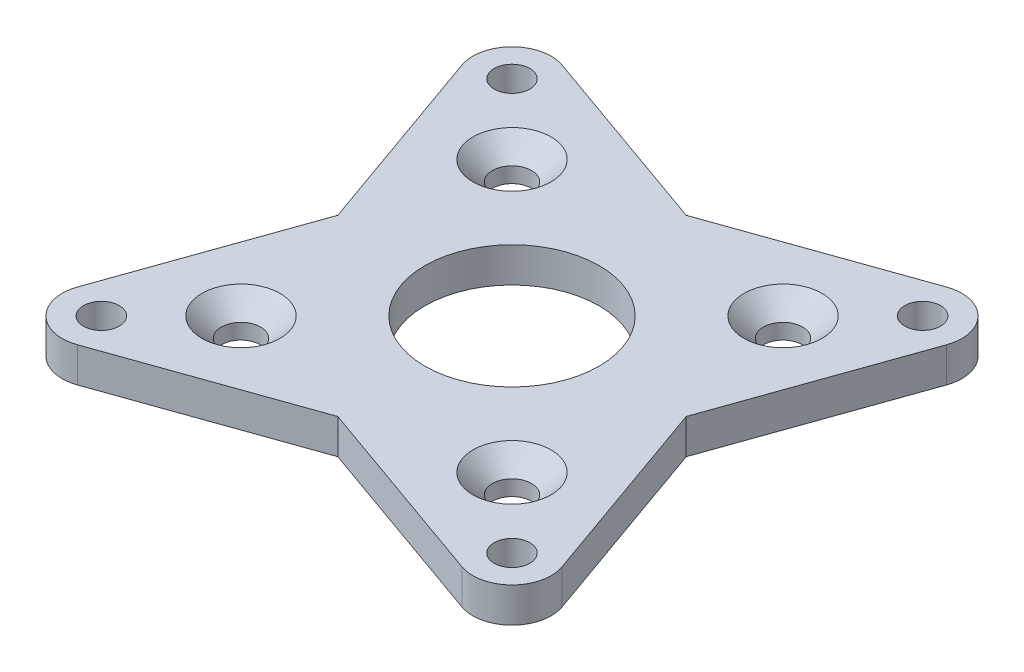
SolidWorks part; units mm, degrees
ref_plane "Alzado" through (0, 0, 0) normal (0, 0, 1) x (1, 0, 0)
ref_plane "Planta" through (0, 0, 0) normal (0, 1, 0) x (1, 0, 0)
ref_plane "Vista lateral" through (0, 0, 0) normal (1, 0, 0) x (0, 0, -1)
sketch "Sketch1" plane through (0, 0, 0) normal (0, 1, 0) x (1, 0, 0)
  line L1 (-35.65, -30) -> (35.65, -30)
  line L2 (-35.65, -30) -> (-35.65, 30)
  line L3 (-35.65, 30) -> (35.65, 30)
  line L4 (35.65, -30) -> (35.65, 30)
  line L5 (-35.65, -30) -> (35.65, 30) construction
  line L6 (-35.65, 30) -> (35.65, -30) construction
  point P0 (0, 0)
  dimension "D1" = 60
  dimension "D2" = 71.3
extrude "Boss-Extrude1" add sketch "Sketch1" along normal blind 4
sketch "Sketch2" plane through (0, 4, 0) normal (0, 1, 0) x (1, 0, 0)
  line L5 (-15.5563, -15.5563) -> (15.5563, -15.5563) construction
  line L6 (-15.5563, -15.5563) -> (-15.5563, 15.5563) construction
  line L7 (-15.5563, 15.5563) -> (15.5563, 15.5563) construction
  line L8 (15.5563, -15.5563) -> (15.5563, 15.5563) construction
  line L9 (-15.5563, -15.5563) -> (15.5563, 15.5563) construction
  line L10 (-15.5563, 15.5563) -> (15.5563, -15.5563) construction
  line L11 (-23.57, -23.57) -> (23.57, -23.57) construction
  line L12 (-23.57, -23.57) -> (-23.57, 23.57) construction
  line L13 (-23.57, 23.57) -> (23.57, 23.57) construction
  line L14 (23.57, -23.57) -> (23.57, 23.57) construction
  line L15 (-23.57, -23.57) -> (23.57, 23.57) construction
  line L16 (-23.57, 23.57) -> (23.57, -23.57) construction
  circle A2 centre (-15.5563, 15.5563) radius 2.05
  circle A3 centre (-23.57, 23.57) radius 2.05
  circle A4 centre (15.5563, 15.5563) radius 2.05
  circle A5 centre (23.57, 23.57) radius 2.05
  circle A6 centre (15.5563, -15.5563) radius 2.05
  circle A7 centre (23.57, -23.57) radius 2.05
  circle A8 centre (-15.5563, -15.5563) radius 2.05
  circle A9 centre (-23.57, -23.57) radius 2.05
  point P0 (0, 0)
  point P29 (0, 0)
  dimension "D1" = 47.14
  dimension "D2" = 44
  dimension "D3" = 4.1
  dimension "D4" = 4
extrude "Cut-Extrude1" cut sketch "Sketch2" against normal through all
sketch "Sketch3" plane through (0, 4, 0) normal (0, 1, 0) x (1, 0, 0)
  circle A0 centre (-15.5563, 15.5563) radius 3.6
  circle A1 centre (15.5563, 15.5563) radius 3.6
  circle A2 centre (15.5563, -15.5563) radius 3.6
  circle A3 centre (-15.5563, -15.5563) radius 3.6
  point P12 (0, 0)
  dimension "D1" = 7.2
  dimension "D2" = 4
sketch "Sketch4" plane through (0, 4, 0) normal (0, 1, 0) x (1, 0, 0)
  circle A1 centre (0, 0) radius 10
  dimension "D1" = 20
extrude "Cut-Extrude3" cut sketch "Sketch4" against normal through all
sketch "Sketch5" plane through (0, 4, 0) normal (0, 1, 0) x (1, 0, 0)
  line L0 (20, 0) -> (27.8121, 22.0683)
  line L1 (22.0683, 27.8121) -> (0, 20)
  line L2 (0, -20) -> (22.0683, -27.8121)
  line L3 (27.8121, -22.0683) -> (20, 0)
  line L4 (-20, 0) -> (-27.8121, -22.0683)
  line L5 (-22.0683, -27.8121) -> (0, -20)
  line L6 (0, 20) -> (-22.0683, 27.8121)
  line L7 (-27.8121, 22.0683) -> (-20, 0)
  arc A1 (27.8121, 22.0683) -> (22.0683, 27.8121) centre (23.57, 23.57) ccw
  circle A2 centre (23.57, 23.57) radius 2.05 construction
  arc A3 (22.0683, -27.8121) -> (27.8121, -22.0683) centre (23.57, -23.57) ccw
  arc A4 (-27.8121, -22.0683) -> (-22.0683, -27.8121) centre (-23.57, -23.57) ccw
  arc A5 (-22.0683, 27.8121) -> (-27.8121, 22.0683) centre (-23.57, 23.57) ccw
  circle A6 centre (0, 0) radius 10 construction
  point P28 (0, 0)
  dimension "D1" = 4.5
  dimension "D2" = 20
  dimension "D3" = 4
extrude "Cut-Extrude4" cut sketch "Sketch5" against normal through all flip side to cut
hole_wizard "CSK for M4 Hex Socket Countersunk Cap Screw1" positions "Sketch6" profile "Sketch7" countersink size "M4" standard "ISO" end condition through all
sketch "Sketch6" plane through (0, 4, 0) normal (0, 1, 0) x (1, 0, 0)
  point P0 (-15.5563, 15.5563)
  point P3 (15.5563, 15.5563)
  point P6 (15.5563, -15.5563)
  point P9 (-15.5563, -15.5563)
sketch "Sketch7" plane through (-15.5563, 4, -15.5563) normal (1, 0, 0) x (0, 0, 1)
  line L0 (0, 0) -> (0, 4)
  line L1 (0, 4) -> (2.25, 4)
  line L2 (2.25, 4) -> (2.25, 2.23)
  line L3 (2.25, 2.23) -> (4.48, 0)
  line L5 (4.48, 0) -> (0, 0)
  line L6 (-2.25, 2.23) -> (-4.48, 0) construction
  line L11 (0, -6.35) -> (0, 107.95) construction
  dimension "Thru Hole Dia." = 4.5
  dimension "Thru Hole Depth" = 4
  dimension "Near C'Sink Dia." = 8.96
  dimension "Near C'Sink Angle" = 90
